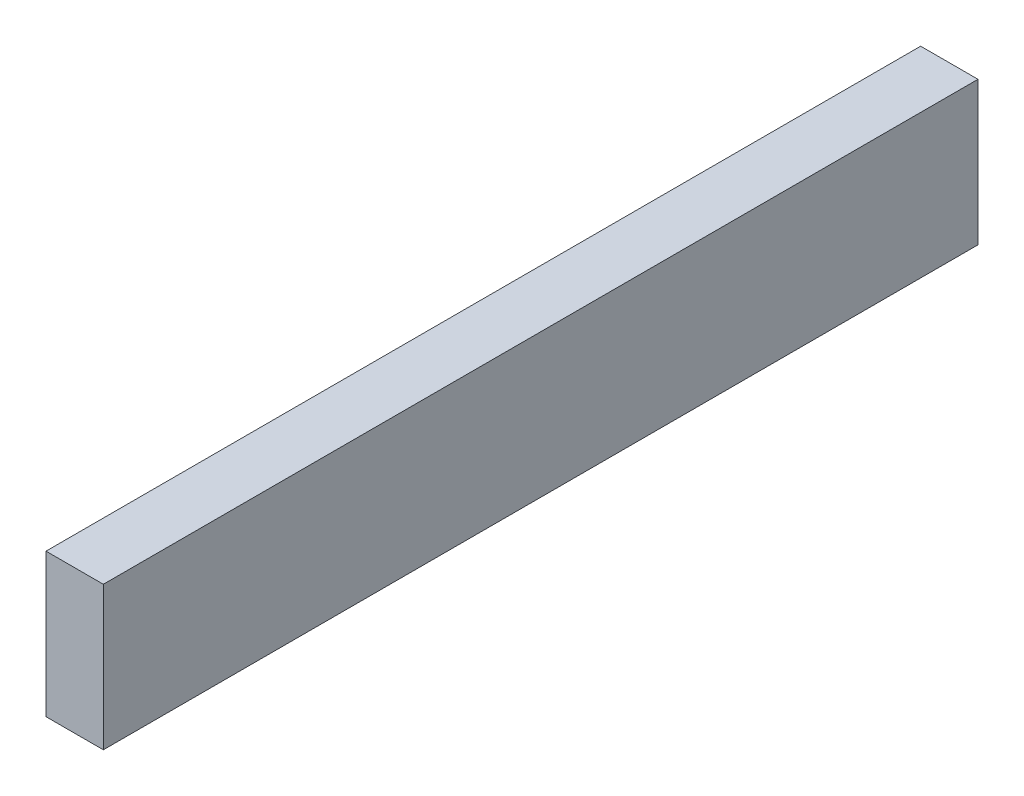
SolidWorks part; units mm, degrees
ref_plane "Alzado" through (0, 0, 0) normal (0, 0, 1) x (1, 0, 0)
ref_plane "Planta" through (0, 0, 0) normal (0, 1, 0) x (1, 0, 0)
ref_plane "Vista lateral" through (0, 0, 0) normal (1, 0, 0) x (0, 0, -1)
sketch "Croquis1" plane through (0, 0, 0) normal (1, 0, 0) x (0, 0, -1)
  line L1 (0, 0) -> (61, 0)
  line L2 (0, 0) -> (0, 10)
  line L3 (0, 10) -> (61, 10)
  line L4 (61, 0) -> (61, 10)
  dimension "D1" = 61
  dimension "D2" = 10
extrude "Saliente-Extruir1" add sketch "Croquis1" along normal blind 4
